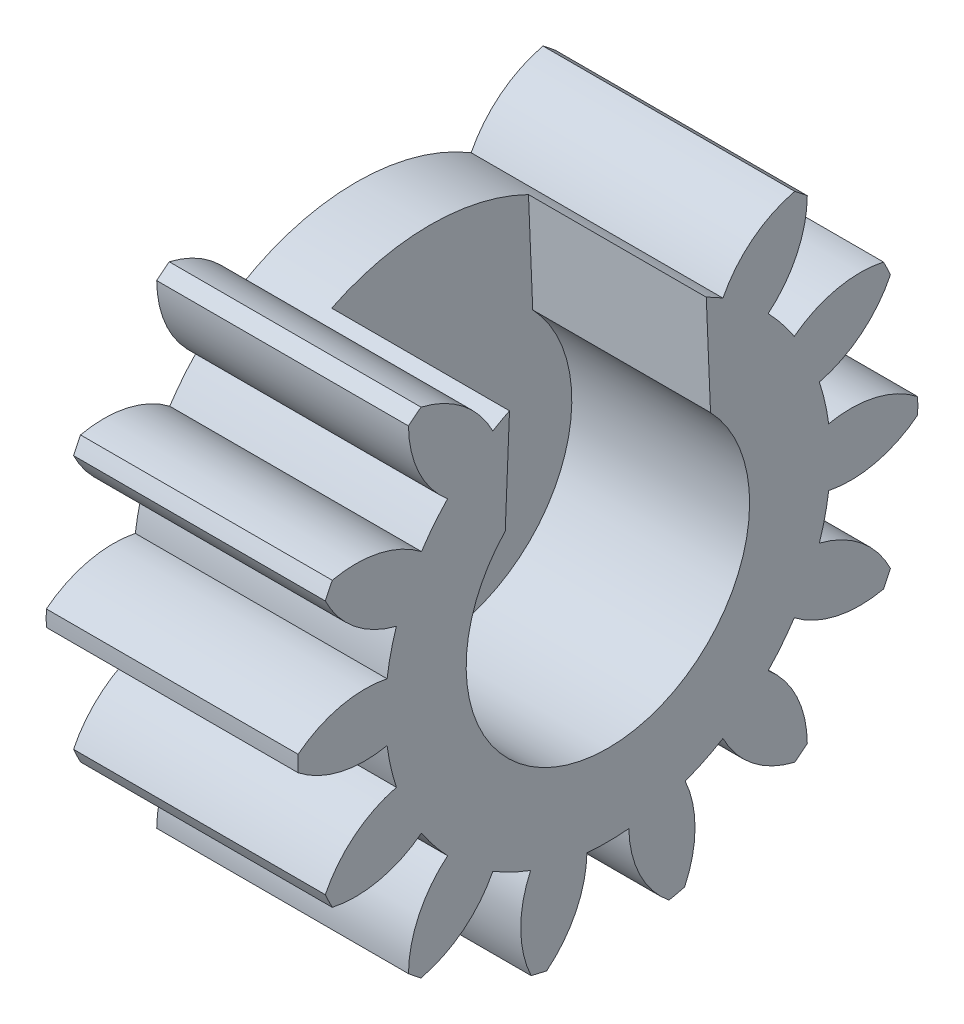
SolidWorks part; units mm, degrees
ref_plane "Front Plane" through (0, 0, 0) normal (0, 0, 1) x (1, 0, 0)
ref_plane "Top Plane" through (0, 0, 0) normal (0, 1, 0) x (1, 0, 0)
ref_plane "Right Plane" through (0, 0, 0) normal (1, 0, 0) x (0, 0, -1)
ref_plane "Plane1" through (-2.2907, 0, 0) normal (1, 0, 0) x (0, 0, -1)
sketch "Sketch1" plane through (-2.2907, 0, 0) normal (1, 0, 0) x (0, 0, -1)
  circle A0 centre (-2.103, 0.6256) radius 2
  arc A1 (-9.2185, -3.0309) -> (-6.9148, -2.5205) centre (-8.6159, -0.2965) ccw
  arc A2 (-6.9148, -2.5205) -> (-6.2409, -3.3655) centre (-2.103, 0.6256) ccw
  arc A3 (-6.2409, -3.3655) -> (-7.2511, -5.4978) centre (-4.4512, -5.5188) ccw
  arc A4 (-7.2511, -5.4978) -> (-6.9273, -5.756) centre (-2.103, 0.6256) ccw
  arc A5 (-6.9273, -5.756) -> (-5.0732, -4.2967) centre (-7.5708, -3.031) ccw
  arc A6 (-5.0732, -4.2967) -> (-4.0995, -4.7656) centre (-2.103, 0.6256) ccw
  arc A7 (-4.0995, -4.7656) -> (-4.0844, -7.1251) centre (-1.5527, -5.9292) ccw
  arc A8 (-4.0844, -7.1251) -> (-3.6807, -7.2173) centre (-2.103, 0.6256) ccw
  arc A9 (-3.6807, -7.2173) -> (-2.6434, -5.0979) centre (-5.4428, -5.0413) ccw
  arc A10 (-2.6434, -5.0979) -> (-1.5626, -5.0979) centre (-2.103, 0.6256) ccw
  arc A11 (-1.5626, -5.0979) -> (-0.5253, -7.2173) centre (1.2368, -5.0413) ccw
  arc A12 (-0.5253, -7.2173) -> (-0.1215, -7.1251) centre (-2.103, 0.6256) ccw
  arc A13 (-0.1215, -7.1251) -> (-0.1065, -4.7656) centre (-2.6533, -5.9292) ccw
  arc A14 (-0.1065, -4.7656) -> (0.8673, -4.2967) centre (-2.103, 0.6256) ccw
  arc A15 (0.8673, -4.2967) -> (2.7214, -5.756) centre (3.3649, -3.031) ccw
  arc A16 (2.7214, -5.756) -> (3.0452, -5.4978) centre (-2.103, 0.6256) ccw
  arc A17 (3.0452, -5.4978) -> (2.0349, -3.3655) centre (0.2452, -5.5188) ccw
  arc A18 (2.0349, -3.3655) -> (2.7088, -2.5205) centre (-2.103, 0.6256) ccw
  arc A19 (2.7088, -2.5205) -> (5.0125, -3.0309) centre (4.4099, -0.2965) ccw
  arc A20 (5.0125, -3.0309) -> (5.1922, -2.6577) centre (-2.103, 0.6256) ccw
  arc A21 (5.1922, -2.6577) -> (3.3568, -1.1748) centre (2.6787, -3.8915) ccw
  arc A22 (3.3568, -1.1748) -> (3.5973, -0.1212) centre (-2.103, 0.6256) ccw
  arc A23 (3.5973, -0.1212) -> (5.8943, 0.4185) centre (4.165, 2.6207) ccw
  arc A24 (5.8943, 0.4185) -> (5.8943, 0.8327) centre (-2.103, 0.6256) ccw
  arc A25 (5.8943, 0.8327) -> (3.5973, 1.3724) centre (4.165, -1.3695) ccw
  arc A26 (3.5973, 1.3724) -> (3.3568, 2.4261) centre (-2.103, 0.6256) ccw
  arc A27 (3.3568, 2.4261) -> (5.1922, 3.909) centre (2.6787, 5.1427) ccw
  arc A28 (5.1922, 3.909) -> (5.0125, 4.2821) centre (-2.103, 0.6256) ccw
  arc A29 (5.0125, 4.2821) -> (2.7088, 3.7717) centre (4.4099, 1.5477) ccw
  arc A30 (2.7088, 3.7717) -> (2.0349, 4.6167) centre (-2.103, 0.6256) ccw
  arc A31 (2.0349, 4.6167) -> (3.0452, 6.7491) centre (0.2452, 6.77) ccw
  arc A32 (3.0452, 6.7491) -> (2.7214, 7.0073) centre (-2.103, 0.6256) ccw
  arc A33 (2.7214, 7.0073) -> (0.8673, 5.5479) centre (3.3649, 4.2822) ccw
  arc A34 (0.8673, 5.5479) -> (-0.1065, 6.0168) centre (-2.103, 0.6256) ccw
  arc A35 (-0.1065, 6.0168) -> (-0.1215, 8.3763) centre (-2.6533, 7.1804) ccw
  arc A36 (-0.1215, 8.3763) -> (-0.5253, 8.4685) centre (-2.103, 0.6256) ccw
  arc A37 (-0.5253, 8.4685) -> (-1.5626, 6.3492) centre (1.2368, 6.2925) ccw
  arc A38 (-1.5626, 6.3492) -> (-2.6434, 6.3492) centre (-2.103, 0.6256) ccw
  arc A39 (-2.6434, 6.3492) -> (-3.6807, 8.4685) centre (-5.4428, 6.2925) ccw
  arc A40 (-3.6807, 8.4685) -> (-4.0844, 8.3763) centre (-2.103, 0.6256) ccw
  arc A41 (-4.0844, 8.3763) -> (-4.0995, 6.0168) centre (-1.5527, 7.1804) ccw
  arc A42 (-4.0995, 6.0168) -> (-5.0732, 5.5479) centre (-2.103, 0.6256) ccw
  arc A43 (-5.0732, 5.5479) -> (-6.9273, 7.0073) centre (-7.5708, 4.2822) ccw
  arc A44 (-6.9273, 7.0073) -> (-7.2511, 6.7491) centre (-2.103, 0.6256) ccw
  arc A45 (-7.2511, 6.7491) -> (-6.2409, 4.6167) centre (-4.4512, 6.77) ccw
  arc A46 (-6.2409, 4.6167) -> (-6.9148, 3.7717) centre (-2.103, 0.6256) ccw
  arc A47 (-6.9148, 3.7717) -> (-9.2185, 4.2821) centre (-8.6159, 1.5477) ccw
  arc A48 (-9.2185, 4.2821) -> (-9.3982, 3.909) centre (-2.103, 0.6256) ccw
  arc A49 (-9.3982, 3.909) -> (-7.5628, 2.4261) centre (-6.8846, 5.1427) ccw
  arc A50 (-7.5628, 2.4261) -> (-7.8033, 1.3724) centre (-2.103, 0.6256) ccw
  arc A51 (-7.8033, 1.3724) -> (-10.1003, 0.8327) centre (-8.371, -1.3695) ccw
  arc A52 (-10.1003, 0.8327) -> (-10.1003, 0.4185) centre (-2.103, 0.6256) ccw
  arc A53 (-10.1003, 0.4185) -> (-7.8033, -0.1212) centre (-8.371, 2.6207) ccw
  arc A54 (-7.8033, -0.1212) -> (-7.5628, -1.1748) centre (-2.103, 0.6256) ccw
  arc A55 (-7.5628, -1.1748) -> (-9.3982, -2.6577) centre (-6.8846, -3.8915) ccw
  arc A56 (-9.3982, -2.6577) -> (-9.2185, -3.0309) centre (-2.103, 0.6256) ccw
  dimension "D1" = 4
extrude "Boss-Extrude1" add sketch "Sketch1" against normal blind 5
sketch "Sketch2" plane through (-2.2907, 0, 0) normal (1, 0, 0) x (0, 0, -1)
  line L0 (-2.103, 4.1256) -> (-2.103, 26.1585) construction
  line L1 (-4.253, 15.1256) -> (-4.753, 3.1483)
  line L2 (0.047, 15.1256) -> (0.547, 3.1483)
  arc A0 (-4.753, 3.1483) -> (0.547, 3.1483) centre (-2.103, 0.6256) ccw
  circle A1 centre (-2.103, 5.1256) radius 0.75
  circle A2 centre (-2.103, 7.1256) radius 0.75
  circle A3 centre (-2.103, 9.1256) radius 0.75
  circle A4 centre (-2.103, 11.1256) radius 0.75
  circle A5 centre (-2.103, 13.1256) radius 0.75
  circle A6 centre (-2.103, 15.1256) radius 0.75
  arc A7 (-4.253, 15.1256) -> (0.047, 15.1256) centre (-2.103, 15.0359) cw
  dimension "D1" = 7.3175
  dimension "D3" = 1.5
  dimension "D2" = 4.5
  dimension "D4" = 2.65
  dimension "D5" = 2.15
extrude "Cut-Extrude1" cut sketch "Sketch2" against normal blind 4.59
sketch "Sketch3" plane through (-6.8807, 0, 0) normal (1, 0, 0) x (0, 0, -1)
  line L0 (-4.4283, 5.8834) -> (-5.0374, 8.8523)
  line L1 (-5.0374, 8.8523) -> (0.4134, 8.6657)
  line L2 (0.4134, 8.6657) -> (0.3167, 5.8406)
  arc A0 (0.3167, 5.8406) -> (-4.4283, 5.8834) centre (-2.103, 0.6256) ccw
extrude "Cut-Extrude2" cut sketch "Sketch3" against normal blind 4.59
sketch "Sketch4" plane through (-7.2907, 0, 0) normal (-1, 0, 0) x (0, 0, 1)
  circle A0 centre (2.103, 0.6256) radius 2
  arc A48 (6.9273, 7.0073) -> (5.0732, 5.5479) centre (7.5708, 4.2822) ccw
  arc A49 (5.0732, 5.5479) -> (-0.8673, 5.5479) centre (2.103, 0.6256) ccw
  arc A50 (-0.8673, 5.5479) -> (-2.7214, 7.0073) centre (-3.3649, 4.2822) ccw
  arc A51 (-2.7214, 7.0073) -> (-3.0452, 6.7491) centre (2.103, 0.6256) ccw
  arc A52 (-3.0452, 6.7491) -> (-2.0349, 4.6167) centre (-0.2452, 6.77) ccw
  arc A53 (-2.0349, 4.6167) -> (-2.7088, 3.7717) centre (2.103, 0.6256) ccw
  arc A54 (-2.7088, 3.7717) -> (-5.0125, 4.2821) centre (-4.4099, 1.5477) ccw
  arc A55 (-5.0125, 4.2821) -> (-5.1922, 3.909) centre (2.103, 0.6256) ccw
  arc A56 (-5.1922, 3.909) -> (-3.3568, 2.4261) centre (-2.6787, 5.1427) ccw
  arc A57 (-3.3568, 2.4261) -> (-3.5973, 1.3724) centre (2.103, 0.6256) ccw
  arc A58 (-3.5973, 1.3724) -> (-5.8943, 0.8327) centre (-4.165, -1.3695) ccw
  arc A59 (-5.8943, 0.8327) -> (-5.8943, 0.4185) centre (2.103, 0.6256) ccw
  arc A60 (-5.8943, 0.4185) -> (-3.5973, -0.1212) centre (-4.165, 2.6207) ccw
  arc A61 (-3.5973, -0.1212) -> (-3.3568, -1.1748) centre (2.103, 0.6256) ccw
  arc A62 (-3.3568, -1.1748) -> (-5.1922, -2.6577) centre (-2.6787, -3.8915) ccw
  arc A63 (-5.1922, -2.6577) -> (-5.0125, -3.0309) centre (2.103, 0.6256) ccw
  arc A64 (-5.0125, -3.0309) -> (-2.7088, -2.5205) centre (-4.4099, -0.2965) ccw
  arc A65 (-2.7088, -2.5205) -> (-2.0349, -3.3655) centre (2.103, 0.6256) ccw
  arc A66 (-2.0349, -3.3655) -> (-3.0452, -5.4978) centre (-0.2452, -5.5188) ccw
  arc A67 (-3.0452, -5.4978) -> (-2.7214, -5.756) centre (2.103, 0.6256) ccw
  arc A68 (-2.7214, -5.756) -> (-0.8673, -4.2967) centre (-3.3649, -3.031) ccw
  arc A69 (-0.8673, -4.2967) -> (0.1065, -4.7656) centre (2.103, 0.6256) ccw
  arc A70 (0.1065, -4.7656) -> (0.1215, -7.1251) centre (2.6533, -5.9292) ccw
  arc A71 (0.1215, -7.1251) -> (0.5253, -7.2173) centre (2.103, 0.6256) ccw
  arc A72 (0.5253, -7.2173) -> (1.5626, -5.0979) centre (-1.2368, -5.0413) ccw
  arc A73 (1.5626, -5.0979) -> (2.6434, -5.0979) centre (2.103, 0.6256) ccw
  arc A74 (2.6434, -5.0979) -> (3.6807, -7.2173) centre (5.4428, -5.0413) ccw
  arc A75 (3.6807, -7.2173) -> (4.0844, -7.1251) centre (2.103, 0.6256) ccw
  arc A76 (4.0844, -7.1251) -> (4.0995, -4.7656) centre (1.5527, -5.9292) ccw
  arc A77 (4.0995, -4.7656) -> (5.0732, -4.2967) centre (2.103, 0.6256) ccw
  arc A78 (5.0732, -4.2967) -> (6.9273, -5.756) centre (7.5708, -3.031) ccw
  arc A79 (6.9273, -5.756) -> (7.2511, -5.4978) centre (2.103, 0.6256) ccw
  arc A80 (7.2511, -5.4978) -> (6.2409, -3.3655) centre (4.4512, -5.5188) ccw
  arc A81 (6.2409, -3.3655) -> (6.9148, -2.5205) centre (2.103, 0.6256) ccw
  arc A82 (6.9148, -2.5205) -> (9.2185, -3.0309) centre (8.6159, -0.2965) ccw
  arc A83 (9.2185, -3.0309) -> (9.3982, -2.6577) centre (2.103, 0.6256) ccw
  arc A84 (9.3982, -2.6577) -> (7.5628, -1.1748) centre (6.8846, -3.8915) ccw
  arc A85 (7.5628, -1.1748) -> (7.8033, -0.1212) centre (2.103, 0.6256) ccw
  arc A86 (7.8033, -0.1212) -> (10.1003, 0.4185) centre (8.371, 2.6207) ccw
  arc A87 (10.1003, 0.4185) -> (10.1003, 0.8327) centre (2.103, 0.6256) ccw
  arc A88 (10.1003, 0.8327) -> (7.8033, 1.3724) centre (8.371, -1.3695) ccw
  arc A89 (7.8033, 1.3724) -> (7.5628, 2.4261) centre (2.103, 0.6256) ccw
  arc A90 (7.5628, 2.4261) -> (9.3982, 3.909) centre (6.8846, 5.1427) ccw
  arc A91 (9.3982, 3.909) -> (9.2185, 4.2821) centre (2.103, 0.6256) ccw
  arc A92 (9.2185, 4.2821) -> (6.9148, 3.7717) centre (8.6159, 1.5477) ccw
  arc A93 (6.9148, 3.7717) -> (6.2409, 4.6167) centre (2.103, 0.6256) ccw
  arc A94 (6.2409, 4.6167) -> (7.2511, 6.7491) centre (4.4512, 6.77) ccw
  arc A95 (7.2511, 6.7491) -> (6.9273, 7.0073) centre (2.103, 0.6256) ccw
  arc A96 (6.9273, 7.0073) -> (5.0732, 5.5479) centre (7.5708, 4.2822) ccw
  arc A97 (5.0732, 5.5479) -> (-0.8673, 5.5479) centre (2.103, 0.6256) ccw
  arc A98 (-0.8673, 5.5479) -> (-2.7214, 7.0073) centre (-3.3649, 4.2822) ccw
  arc A99 (-2.7214, 7.0073) -> (-3.0452, 6.7491) centre (2.103, 0.6256) ccw
  arc A100 (-3.0452, 6.7491) -> (-2.0349, 4.6167) centre (-0.2452, 6.77) ccw
  arc A101 (-2.0349, 4.6167) -> (-2.7088, 3.7717) centre (2.103, 0.6256) ccw
  arc A102 (-2.7088, 3.7717) -> (-5.0125, 4.2821) centre (-4.4099, 1.5477) ccw
  arc A103 (-5.0125, 4.2821) -> (-5.1922, 3.909) centre (2.103, 0.6256) ccw
  arc A104 (-5.1922, 3.909) -> (-3.3568, 2.4261) centre (-2.6787, 5.1427) ccw
  arc A105 (-3.3568, 2.4261) -> (-3.5973, 1.3724) centre (2.103, 0.6256) ccw
  arc A106 (-3.5973, 1.3724) -> (-5.8943, 0.8327) centre (-4.165, -1.3695) ccw
  arc A107 (-5.8943, 0.8327) -> (-5.8943, 0.4185) centre (2.103, 0.6256) ccw
  arc A108 (-5.8943, 0.4185) -> (-3.5973, -0.1212) centre (-4.165, 2.6207) ccw
  arc A109 (-3.5973, -0.1212) -> (-3.3568, -1.1748) centre (2.103, 0.6256) ccw
  arc A110 (-3.3568, -1.1748) -> (-5.1922, -2.6577) centre (-2.6787, -3.8915) ccw
  arc A111 (-5.1922, -2.6577) -> (-5.0125, -3.0309) centre (2.103, 0.6256) ccw
  arc A112 (-5.0125, -3.0309) -> (-2.7088, -2.5205) centre (-4.4099, -0.2965) ccw
  arc A113 (-2.7088, -2.5205) -> (-2.0349, -3.3655) centre (2.103, 0.6256) ccw
  arc A114 (-2.0349, -3.3655) -> (-3.0452, -5.4978) centre (-0.2452, -5.5188) ccw
  arc A115 (-3.0452, -5.4978) -> (-2.7214, -5.756) centre (2.103, 0.6256) ccw
  arc A116 (-2.7214, -5.756) -> (-0.8673, -4.2967) centre (-3.3649, -3.031) ccw
  arc A117 (-0.8673, -4.2967) -> (0.1065, -4.7656) centre (2.103, 0.6256) ccw
  arc A118 (0.1065, -4.7656) -> (0.1215, -7.1251) centre (2.6533, -5.9292) ccw
  arc A119 (0.1215, -7.1251) -> (0.5253, -7.2173) centre (2.103, 0.6256) ccw
  arc A120 (0.5253, -7.2173) -> (1.5626, -5.0979) centre (-1.2368, -5.0413) ccw
  arc A121 (1.5626, -5.0979) -> (2.6434, -5.0979) centre (2.103, 0.6256) ccw
  arc A122 (2.6434, -5.0979) -> (3.6807, -7.2173) centre (5.4428, -5.0413) ccw
  arc A123 (3.6807, -7.2173) -> (4.0844, -7.1251) centre (2.103, 0.6256) ccw
  arc A124 (4.0844, -7.1251) -> (4.0995, -4.7656) centre (1.5527, -5.9292) ccw
  arc A125 (4.0995, -4.7656) -> (5.0732, -4.2967) centre (2.103, 0.6256) ccw
  arc A126 (5.0732, -4.2967) -> (6.9273, -5.756) centre (7.5708, -3.031) ccw
  arc A127 (6.9273, -5.756) -> (7.2511, -5.4978) centre (2.103, 0.6256) ccw
  arc A128 (7.2511, -5.4978) -> (6.2409, -3.3655) centre (4.4512, -5.5188) ccw
  arc A129 (6.2409, -3.3655) -> (6.9148, -2.5205) centre (2.103, 0.6256) ccw
  arc A130 (6.9148, -2.5205) -> (9.2185, -3.0309) centre (8.6159, -0.2965) ccw
  arc A131 (9.2185, -3.0309) -> (9.3982, -2.6577) centre (2.103, 0.6256) ccw
  arc A132 (9.3982, -2.6577) -> (7.5628, -1.1748) centre (6.8846, -3.8915) ccw
  arc A133 (7.5628, -1.1748) -> (7.8033, -0.1212) centre (2.103, 0.6256) ccw
  arc A134 (7.8033, -0.1212) -> (10.1003, 0.4185) centre (8.371, 2.6207) ccw
  arc A135 (10.1003, 0.4185) -> (10.1003, 0.8327) centre (2.103, 0.6256) ccw
  arc A136 (10.1003, 0.8327) -> (7.8033, 1.3724) centre (8.371, -1.3695) ccw
  arc A137 (7.8033, 1.3724) -> (7.5628, 2.4261) centre (2.103, 0.6256) ccw
  arc A138 (7.5628, 2.4261) -> (9.3982, 3.909) centre (6.8846, 5.1427) ccw
  arc A139 (9.3982, 3.909) -> (9.2185, 4.2821) centre (2.103, 0.6256) ccw
  arc A140 (9.2185, 4.2821) -> (6.9148, 3.7717) centre (8.6159, 1.5477) ccw
  arc A141 (6.9148, 3.7717) -> (6.2409, 4.6167) centre (2.103, 0.6256) ccw
  arc A142 (6.2409, 4.6167) -> (7.2511, 6.7491) centre (4.4512, 6.77) ccw
  arc A143 (7.2511, 6.7491) -> (6.9273, 7.0073) centre (2.103, 0.6256) ccw
  dimension "D1" = 0
extrude "Boss-Extrude2" add sketch "Sketch4" along normal blind 1.5
sketch "Sketch5" plane through (-6.8807, 0, 0) normal (1, 0, 0) x (0, 0, -1)
  circle A0 centre (-2.103, 0.6256) radius 1.1
  circle A1 centre (-2.103, 0.6256) radius 2
  dimension "D1" = 2.2
extrude "Boss-Extrude3" add sketch "Sketch5" against normal through all
